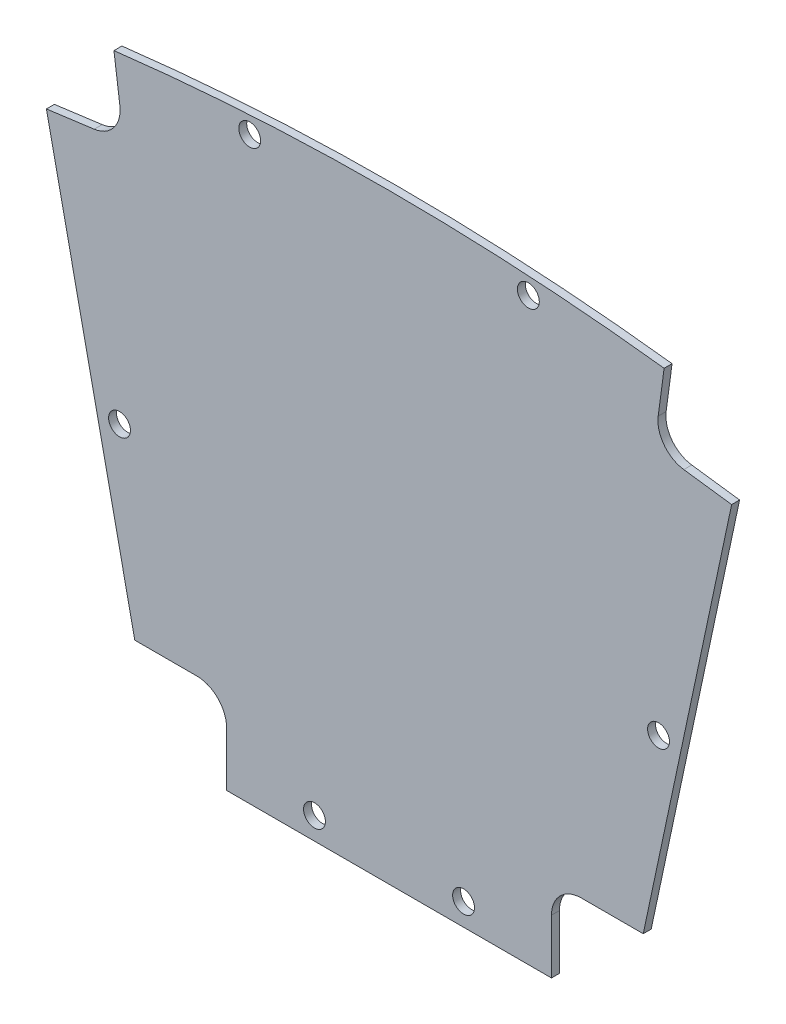
SolidWorks part; units mm, degrees
ref_plane "Front Plane" through (0, 0, 0) normal (0, 0, 1) x (1, 0, 0)
ref_plane "Top Plane" through (0, 0, 0) normal (0, 1, 0) x (1, 0, 0)
ref_plane "Right Plane" through (0, 0, 0) normal (1, 0, 0) x (0, 0, -1)
sketch "Sketch1" plane through (0, 0, 0) normal (0, 0, 1) x (1, 0, 0)
  line L0 (-20, -60.7941) -> (0, -60.7941) construction
  line L1 (-55.3628, 57.8178) -> (-54.1729, 48.874)
  line L2 (-20, -60.7941) -> (-33.695, -60.7941) construction
  line L3 (-33.695, -60.7941) -> (-33.695, -48.8456) construction
  line L4 (-51.9733, -43.8456) -> (-58.5797, -12.7647) construction
  line L5 (-38.695, -43.8456) -> (-51.9733, -43.8456) construction
  line L6 (-58.5797, -12.7647) -> (-68.0056, 31.5807) construction
  line L7 (-68.0056, 31.5807) -> (-70.1572, 41.7032) construction
  line L8 (-56.4875, 58.6887) -> (-55.1641, 48.7421) construction
  line L9 (-59.4611, 43.1263) -> (-70.1572, 41.7032) construction
  line L10 (-59.3292, 42.1351) -> (-68.9545, 40.8544)
  line L11 (-67.0275, 31.7886) -> (-68.9545, 40.8544)
  line L12 (-57.6015, -12.5568) -> (-67.0275, 31.7886)
  line L13 (-51.1635, -42.8456) -> (-57.6015, -12.5568)
  line L14 (-38.695, -42.8456) -> (-51.1635, -42.8456)
  line L15 (-32.695, -59.7941) -> (-32.695, -48.8456)
  line L16 (-20, -59.7941) -> (-32.695, -59.7941)
  line L17 (-20, -59.7941) -> (0, -59.7941)
  line L18 (59.4611, 43.1263) -> (70.1572, 41.7032) construction
  line L19 (56.4875, 58.6887) -> (55.1641, 48.7421) construction
  line L20 (68.0056, 31.5807) -> (70.1572, 41.7032) construction
  line L21 (58.5797, -12.7647) -> (68.0056, 31.5807) construction
  line L22 (38.695, -43.8456) -> (51.9733, -43.8456) construction
  line L23 (51.9733, -43.8456) -> (58.5797, -12.7647) construction
  line L24 (33.695, -60.7941) -> (33.695, -48.8456) construction
  line L25 (20, -60.7941) -> (33.695, -60.7941) construction
  line L26 (20, -60.7941) -> (0, -60.7941) construction
  line L27 (20, -59.7941) -> (0, -59.7941)
  line L28 (20, -59.7941) -> (32.695, -59.7941)
  line L29 (32.695, -59.7941) -> (32.695, -48.8456)
  line L30 (38.695, -42.8456) -> (51.1635, -42.8456)
  line L31 (51.1635, -42.8456) -> (57.6015, -12.5568)
  line L32 (57.6015, -12.5568) -> (67.0275, 31.7886)
  line L33 (67.0275, 31.7886) -> (68.9545, 40.8544)
  line L34 (59.3292, 42.1351) -> (68.9545, 40.8544)
  line L35 (55.3628, 57.8178) -> (54.1729, 48.874)
  circle A0 centre (-28.0398, 56.8533) radius 2.2
  circle A1 centre (-54.2394, -6.7304) radius 2.2
  circle A2 centre (-15, -55.2941) radius 2.2
  arc A3 (-33.695, -48.8456) -> (-38.695, -43.8456) centre (-38.695, -48.8456) ccw construction
  arc A4 (-55.1641, 48.7421) -> (-59.4611, 43.1263) centre (-60.1205, 48.0826) cw construction
  arc A5 (0, 62.1325) -> (-56.4875, 58.6887) centre (0, -402.8675) ccw construction
  arc A6 (0, 61.1325) -> (-55.3628, 57.8178) centre (0, -402.8675) ccw
  arc A7 (-54.1729, 48.874) -> (-59.3292, 42.1351) centre (-60.1205, 48.0826) cw
  arc A8 (-32.695, -48.8456) -> (-38.695, -42.8456) centre (-38.695, -48.8456) ccw
  arc A9 (0, 62.1325) -> (56.4875, 58.6887) centre (0, -402.8675) cw construction
  arc A10 (55.1641, 48.7421) -> (59.4611, 43.1263) centre (60.1205, 48.0826) ccw construction
  arc A11 (33.695, -48.8456) -> (38.695, -43.8456) centre (38.695, -48.8456) cw construction
  arc A12 (32.695, -48.8456) -> (38.695, -42.8456) centre (38.695, -48.8456) cw
  arc A13 (54.1729, 48.874) -> (59.3292, 42.1351) centre (60.1205, 48.0826) ccw
  arc A14 (0, 61.1325) -> (55.3628, 57.8178) centre (0, -402.8675) cw
  circle A15 centre (15, -55.2941) radius 2.2
  circle A16 centre (54.2394, -6.7304) radius 2.2
  circle A17 centre (28.0398, 56.8533) radius 2.2
extrude "Boss-Extrude1" add sketch "Sketch1" along normal blind 1.6
